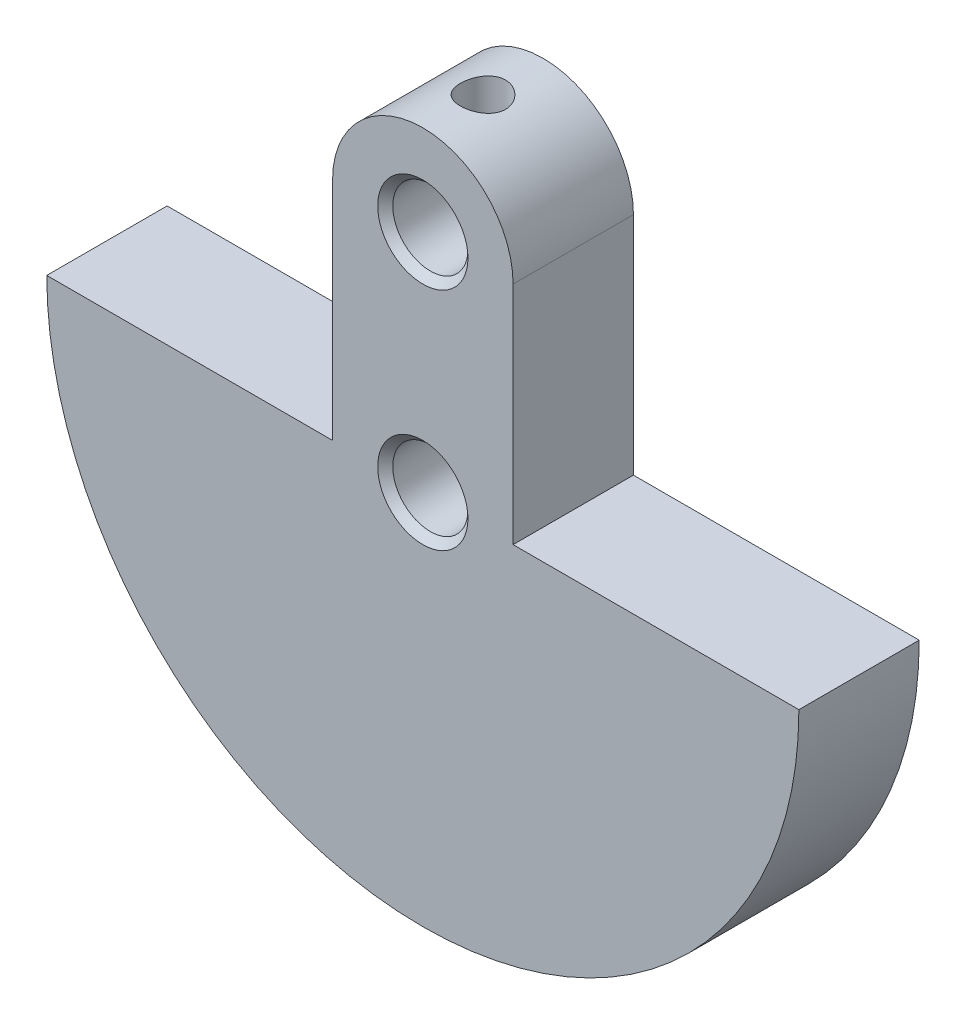
SolidWorks part; units mm, degrees
ref_plane "Front Plane" through (0, 0, 0) normal (0, 0, 1) x (1, 0, 0)
ref_plane "Top Plane" through (0, 0, 0) normal (0, 1, 0) x (1, 0, 0)
ref_plane "Right Plane" through (0, 0, 0) normal (1, 0, 0) x (0, 0, -1)
sketch "Sketch1" plane through (0, 0, 0) normal (0, 0, 1) x (1, 0, 0)
  line L0 (-6, 15) -> (-6, 0)
  line L1 (-6, 0) -> (-25, 0)
  line L2 (6, 15) -> (6, 0)
  line L3 (6, 0) -> (25, 0)
  arc A0 (-25, 0) -> (25, 0) centre (0, 0) ccw
  arc A1 (6, 15) -> (-6, 15) centre (0, 15) ccw
  circle A2 centre (0, 15) radius 2.5
  circle A3 centre (0, 0) radius 2.5
  dimension "D1" = 50
  dimension "D2" = 12
  dimension "D4" = 5
  dimension "D3" = 15
extrude "Boss-Extrude1" add sketch "Sketch1" along normal blind 8
chamfer "Chamfer1" distance 0.5 angle 45 2 edges at (2.5, 15, 8) (2.5, 0, 8)
ref_plane "Plane1" through (0, 21, 0) normal (0, 1, 0) x (1, 0, 0)
sketch "Sketch2" plane through (0, 21, 0) normal (0, 1, 0) x (1, 0, 0)
  line L0 (6, 0) -> (-6, 0) construction
  circle A0 centre (0, -4) radius 1.5
  dimension "D1" = 3
  dimension "D2" = 4
extrude "Cut-Extrude1" cut sketch "Sketch2" against normal blind 5
